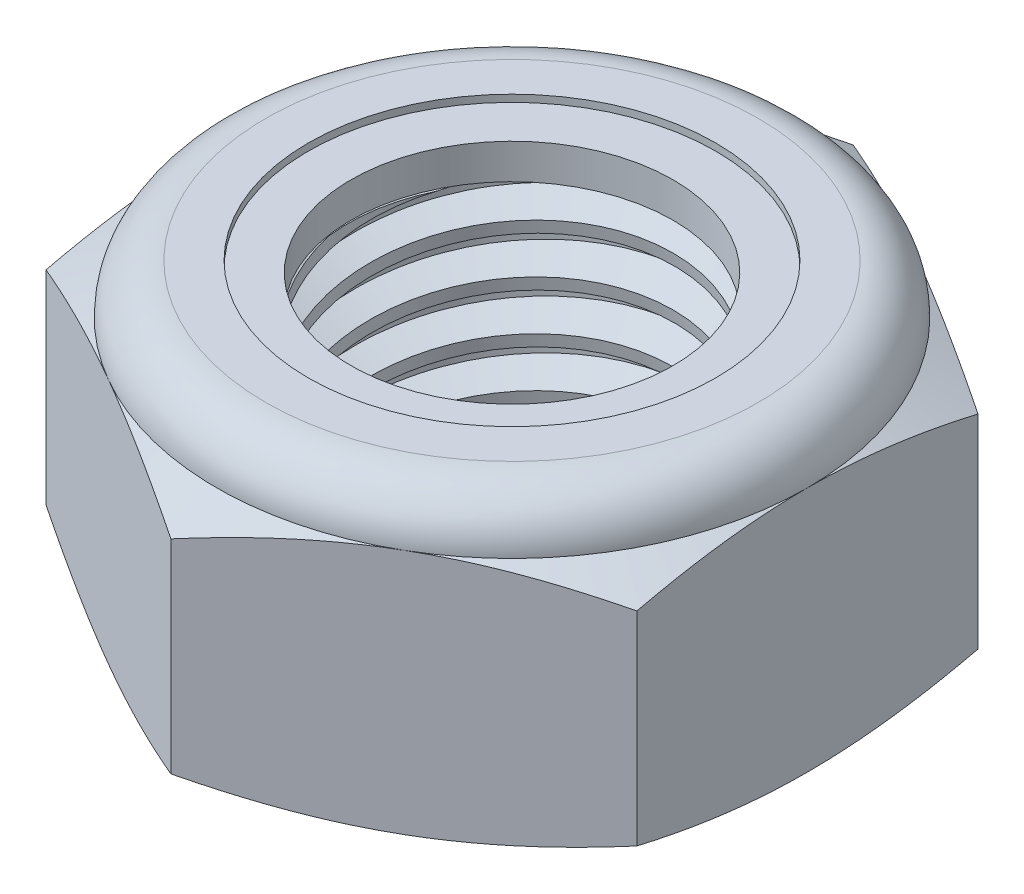
SolidWorks part; units mm, degrees
ref_plane "Front" through (0, 0, 0) normal (0, 0, 1) x (1, 0, 0)
ref_plane "Top" through (0, 0, 0) normal (0, 1, 0) x (1, 0, 0)
ref_plane "Right" through (0, 0, 0) normal (1, 0, 0) x (0, 0, -1)
sketch "Sketch1" plane through (0, 0, 0) normal (0, 1, 0) x (1, 0, 0)
  line L1 (0, 7.3323) -> (-6.35, 3.6662)
  line L2 (-6.35, 3.6662) -> (-6.35, -3.6662)
  line L3 (-6.35, -3.6662) -> (0, -7.3323)
  line L4 (0, -7.3323) -> (6.35, -3.6662)
  line L5 (6.35, -3.6662) -> (6.35, 3.6662)
  line L6 (6.35, 3.6662) -> (0, 7.3323)
  circle A0 centre (0, 0) radius 6.35 construction
  dimension "Hex Flats" = 12.7
extrude "Extrude1" add sketch "Sketch1" along normal blind 6.35
sketch "Sketch2" plane through (0, 0, 0) normal (1, 0, 0) x (0, 0, -1)
  line L0 (-3.9688, 0) -> (-3.9688, 6.35) construction
  line L1 (0, 0) -> (3.9688, 0)
  line L2 (0, 0) -> (0, 6.35)
  line L3 (0, 6.35) -> (3.9688, 6.35)
  line L4 (3.9688, 0) -> (3.9688, 6.35)
  line L5 (-3.6662, 6.35) -> (3.6662, 6.35) construction
  line L7 (0, -3.9688) -> (0, 0) construction
  dimension "Thread Dia" = 7.9375
revolve "Revolve1" add sketch "Sketch2" angle 360 about L7
sketch "Sketch3" plane through (0, 0, 0) normal (1, 0, 0) x (0, 0, -1)
  line L0 (3.9688, 6.35) -> (-3.9688, 6.35) construction
  line L1 (-3.9688, 6.35) -> (-3.9688, 5.2917) construction
  line L2 (-3.9688, 5.2917) -> (3.9688, 6.35) construction
  line L3 (3.9688, 6.35) -> (3.9862, 6.2189) construction
  line L4 (3.9862, 6.2189) -> (4.1086, 5.301)
  line L5 (4.1086, 5.301) -> (3.4971, 5.5531)
  line L6 (3.4971, 5.5531) -> (3.4621, 5.8153)
  line L7 (3.4621, 5.8153) -> (3.9862, 6.2189)
  line L8 (3.4796, 5.6842) -> (4.0474, 5.7599) construction
  line L9 (3.9688, 6.35) -> (3.9688, 5.7494) construction
  line L10 (3.9688, 5.7494) -> (-3.9688, 4.6911) construction
  line L11 (-3.9688, 4.6911) -> (-3.9688, 5.2917) construction
  line L12 (-0.1506, 6.35) -> (0.1506, 4.0905) construction
  line L13 (-3.9688, 0) -> (-3.9688, 6.35) construction
  line L14 (0, 6.35) -> (3.9688, 6.35) construction
  line L15 (3.9688, 0) -> (3.9688, 6.35) construction
  point P13 (0, 5.2203)
  dimension "D1" = 0.1323
  dimension "D2" = 0.2646
  dimension "Thread Pitch" = 1.0583
  dimension "D4" = 60
  dimension "D5" = 1.0583
revolve "Cut-Revolve1" cut sketch "Sketch3" angle 360 about L12
pattern_linear "LPattern1" count 6 spacing 1.0583 along (0, -1, 0) count 2 spacing 1.0583 along (0, 1, 0) of "Cut-Revolve1"
sketch "Sketch4" plane through (0, 0, 0) normal (1, 0, 0) x (0, 0, -1)
  line L0 (0, 6.35) -> (3.9688, 6.35)
  line L1 (3.9688, 6.35) -> (3.4621, 6.1138)
  line L2 (3.4621, 6.1138) -> (3.4621, 0.2362)
  line L3 (3.4621, 0.2362) -> (3.9688, 0)
  line L4 (3.9688, 0) -> (0, 0)
  line L5 (0, 0) -> (0, 6.35)
  line L6 (3.9688, 0) -> (3.9688, 6.35) construction
  line L7 (0, 6.35) -> (3.9688, 6.35) construction
  line L8 (0, 0) -> (3.9688, 0) construction
  line L9 (0, 0) -> (0, 6.35) construction
  line L10 (0, 6.35) -> (0, 6.909) construction
  dimension "D1" = 25
revolve "Cut-Revolve2" cut sketch "Sketch4" angle 360 about L10
combine bodies "Combine1" operation type subtract main body 112 bodies to subtract 111
sketch "Sketch5" plane through (0, 0, 0) normal (1, 0, 0) x (0, 0, -1)
  line L0 (0, 0) -> (6.35, 0)
  line L1 (6.35, 0) -> (7.3323, 0.4581)
  line L2 (7.3323, 0.4581) -> (7.3323, 4.8336)
  line L3 (7.3323, 4.8336) -> (6.35, 5.2917)
  line L4 (5.2917, 6.35) -> (5.2917, 7.62)
  line L5 (5.2917, 7.62) -> (8.6023, 7.62)
  line L6 (8.6023, 7.62) -> (8.6023, -1.27)
  line L7 (8.6023, -1.27) -> (0, -1.27)
  line L8 (0, -1.27) -> (0, 0)
  line L9 (6.35, 5.2917) -> (6.35, 0) construction
  line L10 (0, 0) -> (3.9688, 0) construction
  line L13 (7.3323, 2.6458) -> (8.6023, 2.6458) construction
  line L14 (7.3323, 6.35) -> (7.3323, 0) construction
  line L15 (0, 0) -> (0, 7.62) construction
  line L20 (0, 7.62) -> (5.2917, 7.62) construction
  line L22 (0, 6.35) -> (3.9688, 6.35) construction
  arc A0 (6.35, 5.2917) -> (5.2917, 6.35) centre (5.2917, 5.2917) ccw
  dimension "D1" = 25
  dimension "D2" = 1.27
  dimension "D3" = 6.35
  dimension "D4" = 1.0583
revolve "Cut-Revolve3" cut sketch "Sketch5" angle 360 about L15
sketch "Sketch6" plane through (0, 0, 0) normal (1, 0, 0) x (0, 0, -1)
  line L0 (0, 5.2917) -> (6.1976, 5.2917)
  line L1 (5.2917, 6.1976) -> (4.3769, 6.1976)
  line L2 (0, 7.62) -> (0, 5.2917)
  line L3 (4.3769, 7.62) -> (0, 7.62)
  line L4 (0, 7.62) -> (5.2917, 7.62) construction
  line L5 (0, 0) -> (0, 7.62) construction
  line L6 (0, 7.62) -> (0, 44.323) construction
  line L7 (4.3769, 6.1976) -> (4.3769, 7.62)
  line L8 (5.2917, 6.35) -> (5.2917, 6.1976) construction
  line L9 (4.3769, 6.1976) -> (3.4621, 6.1976) construction
  line L10 (3.4621, 6.1976) -> (3.4621, 6.1138) construction
  arc A0 (6.1976, 5.2917) -> (5.2917, 6.1976) centre (5.2917, 5.2917) ccw
  arc A1 (6.35, 5.2917) -> (5.2917, 6.35) centre (5.2917, 5.2917) ccw construction
  dimension "D1" = 0.1524
revolve "Cut-Revolve4" cut sketch "Sketch6" angle 360 about L6
sketch "Sketch7" plane through (0, 0, 0) normal (1, 0, 0) x (0, 0, -1)
  line L0 (3.4621, 5.3679) -> (6.1179, 5.3679)
  line L1 (5.2917, 6.1214) -> (3.4621, 6.1214)
  line L2 (3.4621, 6.1214) -> (3.4621, 5.3679)
  line L3 (3.4621, 5.3679) -> (0, 5.3679) construction
  line L4 (0, 5.3679) -> (0, 6.1214) construction
  line L5 (0, 6.1214) -> (3.4621, 6.1214) construction
  line L6 (3.4621, 5.3679) -> (3.4621, 5.2917) construction
  line L7 (0, 5.2917) -> (6.1976, 5.2917) construction
  line L8 (5.2917, 6.1214) -> (5.2917, 6.1976) construction
  arc A0 (6.1179, 5.3679) -> (5.2917, 6.1214) centre (5.2917, 5.2917) ccw
  arc A2 (6.1976, 5.2917) -> (5.2917, 6.1976) centre (5.2917, 5.2917) ccw construction
  dimension "D1" = 0.0762
revolve "Revolve2" add sketch "Sketch7" angle 360 about L4
equation "\"D1@Sketch3\"=\"Thread Pitch@Sketch3\"/8"
equation "\"D2@Sketch3\"=\"Thread Pitch@Sketch3\"/4"
equation "\"D5@Sketch3\"=\"Thread Pitch@Sketch3\""
equation "\"D4@LPattern1\"=\"Thread Pitch@Sketch3\""
equation "\"D3@LPattern1\"=\"Thread Pitch@Sketch3\""
equation "\"D1@LPattern1\"=\"Height@Extrude1\"/\"Thread Pitch@Sketch3\""
equation "\"D4@Sketch5\"=\"Height@Extrude1\"/6"
